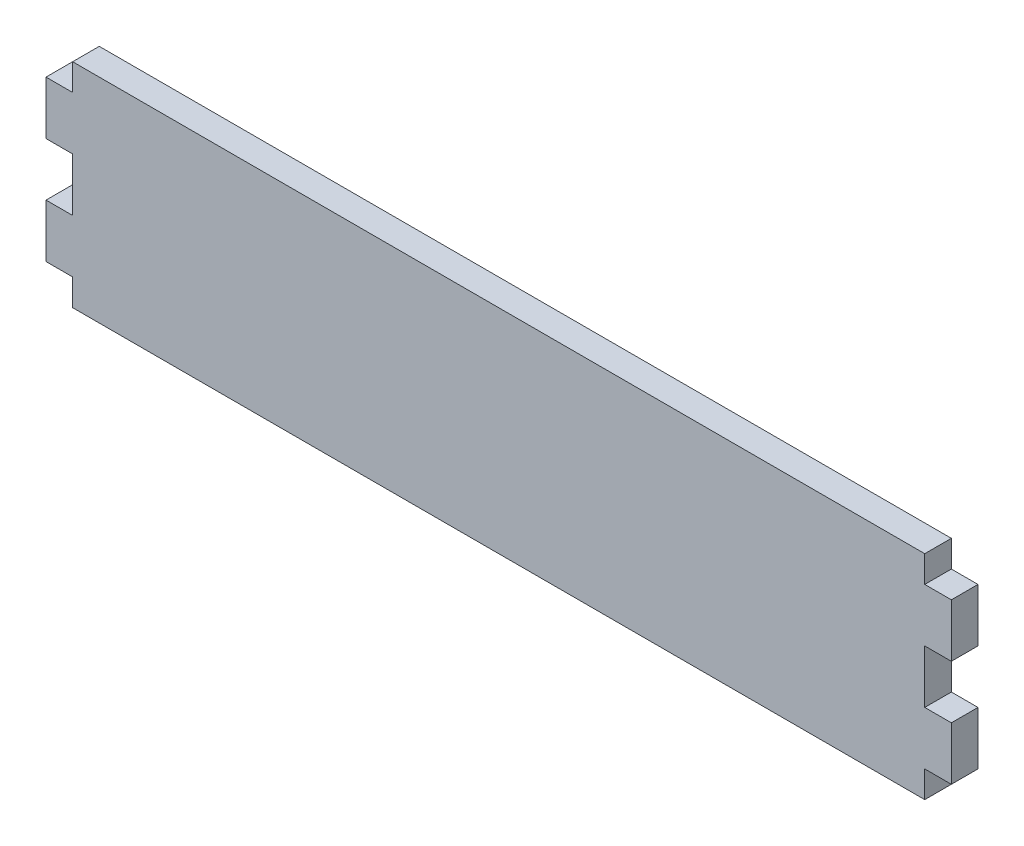
SolidWorks part; units mm, degrees
ref_plane "Front Plane" through (0, 0, 0) normal (0, 0, 1) x (1, 0, 0)
ref_plane "Top Plane" through (0, 0, 0) normal (0, 1, 0) x (1, 0, 0)
ref_plane "Right Plane" through (0, 0, 0) normal (1, 0, 0) x (0, 0, -1)
sketch "Sketch1" plane through (0, 0, 0) normal (0, 0, 1) x (1, 0, 0)
  line L0 (0, 20) -> (0, 0) construction
  line L1 (-40, 0) -> (40, 0)
  line L2 (40, 7.5) -> (40, 12.5)
  line L3 (-40, 20) -> (40, 20)
  line L4 (40, 0) -> (40, 2.5)
  line L5 (40, 17.5) -> (42.5, 17.5)
  line L6 (-40, 17.5) -> (-40, 20)
  line L7 (40, 12.5) -> (42.5, 12.5)
  line L8 (42.5, 17.5) -> (42.5, 12.5)
  line L9 (40, 7.5) -> (42.5, 7.5)
  line L10 (-42.5, 7.5) -> (-42.5, 2.5)
  line L11 (40, 2.5) -> (42.5, 2.5)
  line L12 (42.5, 7.5) -> (42.5, 2.5)
  line L13 (40, 17.5) -> (40, 20)
  line L14 (-40, 2.5) -> (-42.5, 2.5)
  line L15 (-40, 7.5) -> (-42.5, 7.5)
  line L16 (-42.5, 17.5) -> (-42.5, 12.5)
  line L17 (-40, 12.5) -> (-42.5, 12.5)
  line L18 (-40, 17.5) -> (-42.5, 17.5)
  line L19 (-40, 0) -> (-40, 2.5)
  line L20 (-40, 7.5) -> (-40, 12.5)
  dimension "D1" = 40
  dimension "D2" = 20
  dimension "D3" = 2.5
  dimension "D4" = 2.5
  dimension "D5" = 5
  dimension "D6" = 5
extrude "Boss-Extrude1" add sketch "Sketch1" along normal blind 2.5
equation "\"t\"=2.5"
equation "\"D3@Sketch1\"=\"t\""
equation "\"D1@Boss-Extrude1\"=\"t\""
